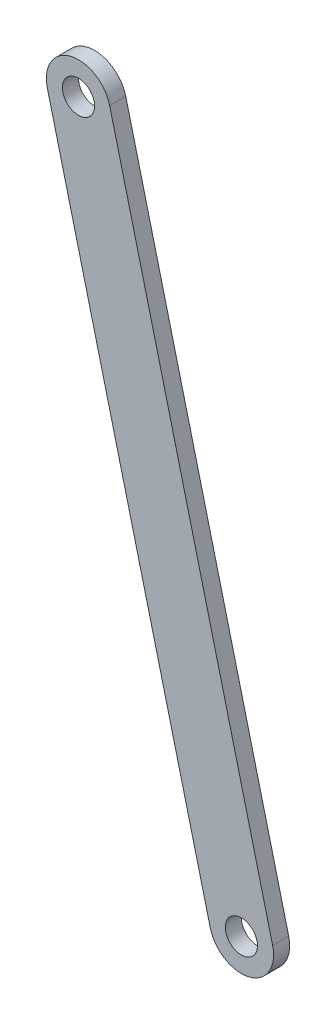
SolidWorks part; units mm, degrees
ref_plane "Front" through (0, 0, 0) normal (0, 0, 1) x (1, 0, 0)
ref_plane "Top" through (0, 0, 0) normal (0, 1, 0) x (1, 0, 0)
ref_plane "Right" through (0, 0, 0) normal (1, 0, 0) x (0, 0, -1)
sketch "Sketch1" plane through (0, 0, 0) normal (0, 0, 1) x (1, 0, 0)
  line L0 (-59.2315, -28.0529) -> (-43.1601, -91.7569) construction
  line L1 (-56.153, -27.2763) -> (-40.0816, -90.9803)
  line L2 (-62.3101, -28.8296) -> (-46.2387, -92.5336)
  arc A0 (-56.153, -27.2763) -> (-62.3101, -28.8296) centre (-59.2315, -28.0529) ccw
  arc A1 (-46.2387, -92.5336) -> (-40.0816, -90.9803) centre (-43.1601, -91.7569) ccw
  circle A2 centre (-43.1601, -91.7569) radius 1.5875
  circle A3 centre (-59.2315, -28.0529) radius 1.5875
  point P4 (-51.1958, -59.9049)
  dimension "D1" = 3.175
  dimension "D2" = 6.35
extrude "Boss-Extrude1" add sketch "Sketch1" along normal blind 1.5875 from offset 1.5875
